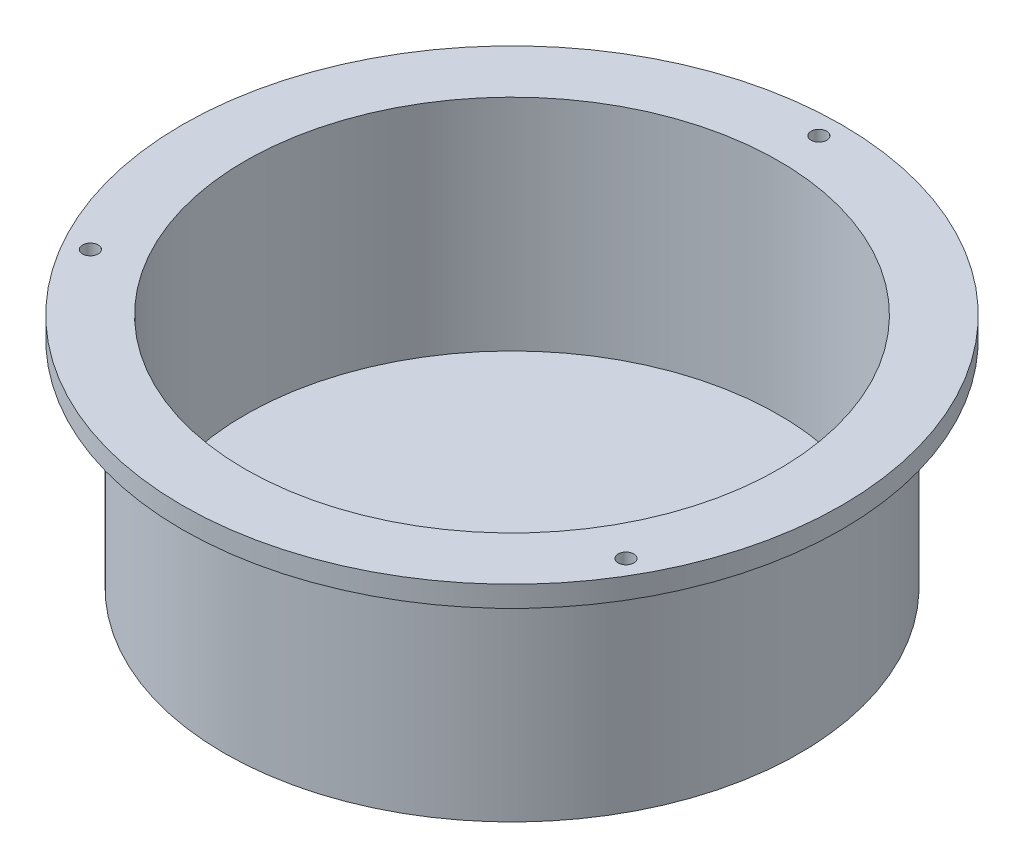
SolidWorks part; units mm, degrees
ref_plane "Front Plane" through (0, 0, 0) normal (0, 0, 1) x (1, 0, 0)
ref_plane "Top Plane" through (0, 0, 0) normal (0, 1, 0) x (1, 0, 0)
ref_plane "Right Plane" through (0, 0, 0) normal (1, 0, 0) x (0, 0, -1)
sketch "Sketch1" plane through (0, 0, 0) normal (0, 1, 0) x (1, 0, 0)
  circle A0 centre (0, 0) radius 55
  dimension "D1" = 110
extrude "Boss-Extrude1" add sketch "Sketch1" along normal blind 41
sketch "Sketch2" plane through (0, 41, 0) normal (0, 1, 0) x (1, 0, 0)
  circle A0 centre (0, 0) radius 63
  dimension "D1" = 126
extrude "Boss-Extrude2" add sketch "Sketch2" along normal blind 4
sketch "Sketch3" plane through (0, 45, 0) normal (0, 1, 0) x (1, 0, 0)
  circle A0 centre (0, 0) radius 51
  dimension "D1" = 102
extrude "Cut-Extrude3" cut sketch "Sketch3" against normal offset from surface (42 mm away) 3 up to face at (0, 0, 55)
sketch "Sketch4" plane through (0, 0, 0) normal (0, -1, 0) x (1, 0, 0)
  circle A0 centre (0, 0) radius 5
  dimension "D1" = 10
extrude "Cut-Extrude4" cut sketch "Sketch4" against normal up to surface (3 mm away) up to face at (0, 3, 51)
sketch "Sketch5" plane through (0, 45, 0) normal (0, 1, 0) x (1, 0, 0)
  circle A0 centre (-0.351, 58.999) radius 1.5
  circle A1 centre (-51.1383, -29.4257) radius 1.5
  circle A2 centre (51.1617, -29.3851) radius 1.5
  dimension "D6" = 3
  dimension "D1" = 59
  dimension "D2" = 59
  dimension "D3" = 59
  dimension "D4" = 102.3
  dimension "D5" = 102.3
extrude "Cut-Extrude5" cut sketch "Sketch5" against normal up to surface (4 mm away) up to face at (0, 41, 55)
